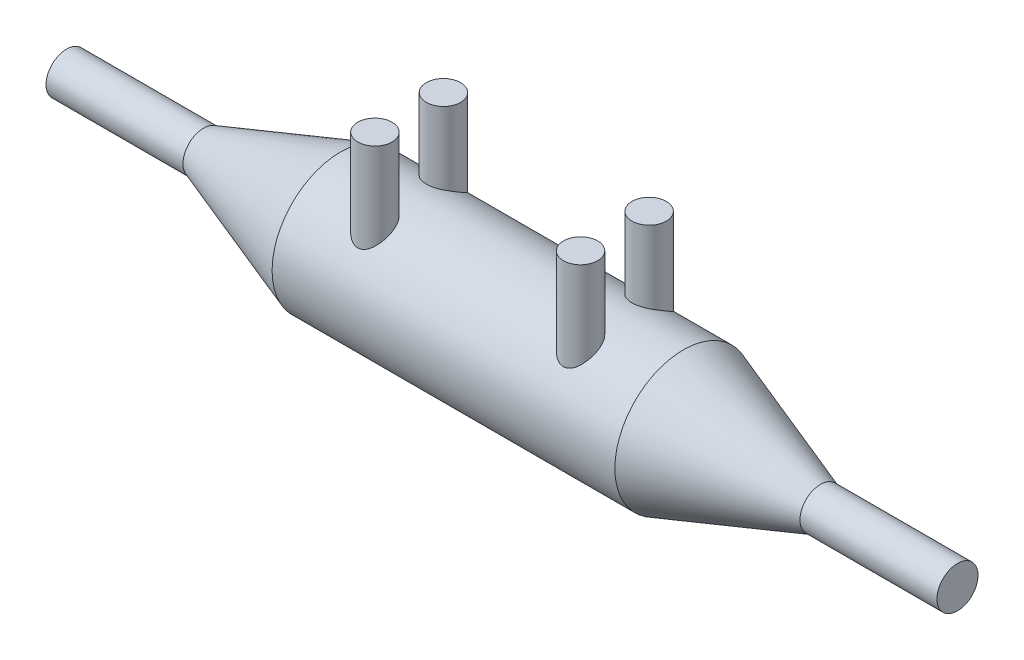
SolidWorks part; units mm, degrees
ref_plane "Front Plane" through (0, 0, 0) normal (0, 0, 1) x (1, 0, 0)
ref_plane "Top Plane" through (0, 0, 0) normal (0, 1, 0) x (1, 0, 0)
ref_plane "Right Plane" through (0, 0, 0) normal (1, 0, 0) x (0, 0, -1)
sketch "Esquisse3" plane through (0, 0, 0) normal (0, 0, 1) x (1, 0, 0)
  line L0 (-30.0767, 0) -> (115.1432, 0) construction
  line L1 (-6.389, -3) -> (13.611, -10)
  line L2 (13.611, -10) -> (63.611, -10)
  line L3 (63.611, -10) -> (83.611, -3)
  line L4 (-6.389, -3) -> (-26.3682, -3)
  line L5 (-26.3682, -3) -> (-26.3682, 0)
  line L6 (-26.3682, 0) -> (103.5902, 0)
  line L7 (83.611, -3) -> (103.5902, -3)
  line L8 (103.5902, -3) -> (103.5902, 0)
  point P5 (0, 0)
  point P8 (0, 0)
  point P10 (0, 0)
  point P14 (120.1432, 0)
  point P15 (0, 0)
  point P16 (-25.0767, 0)
  dimension "D1" = 50
  dimension "D2" = 3
  dimension "D3" = 20
  dimension "D4" = 3
  dimension "D6" = 10
revolve "Révolution1" add sketch "Esquisse3" angle 360 about L0
sketch "Esquisse4" plane through (0, 0, 0) normal (0, 1, 0) x (1, 0, 0)
  line L0 (63.611, -10) -> (63.611, 10) construction
  line L2 (63.611, 0) -> (13.611, 0) construction
  line L3 (13.611, -10) -> (13.611, 10) construction
  line L4 (53.611, -5) -> (23.611, -5) construction
  circle A0 centre (23.611, -5) radius 2.5
  circle A1 centre (53.611, -5) radius 2.5
  circle A2 centre (53.611, 5) radius 2.5
  circle A3 centre (23.611, 5) radius 2.5
  dimension "D3" = 5
  dimension "D1" = 30
  dimension "D2" = 10
  dimension "D4" = 10
extrude "Boss.-Extru.2" add sketch "Esquisse4" along normal blind 20 separate body
